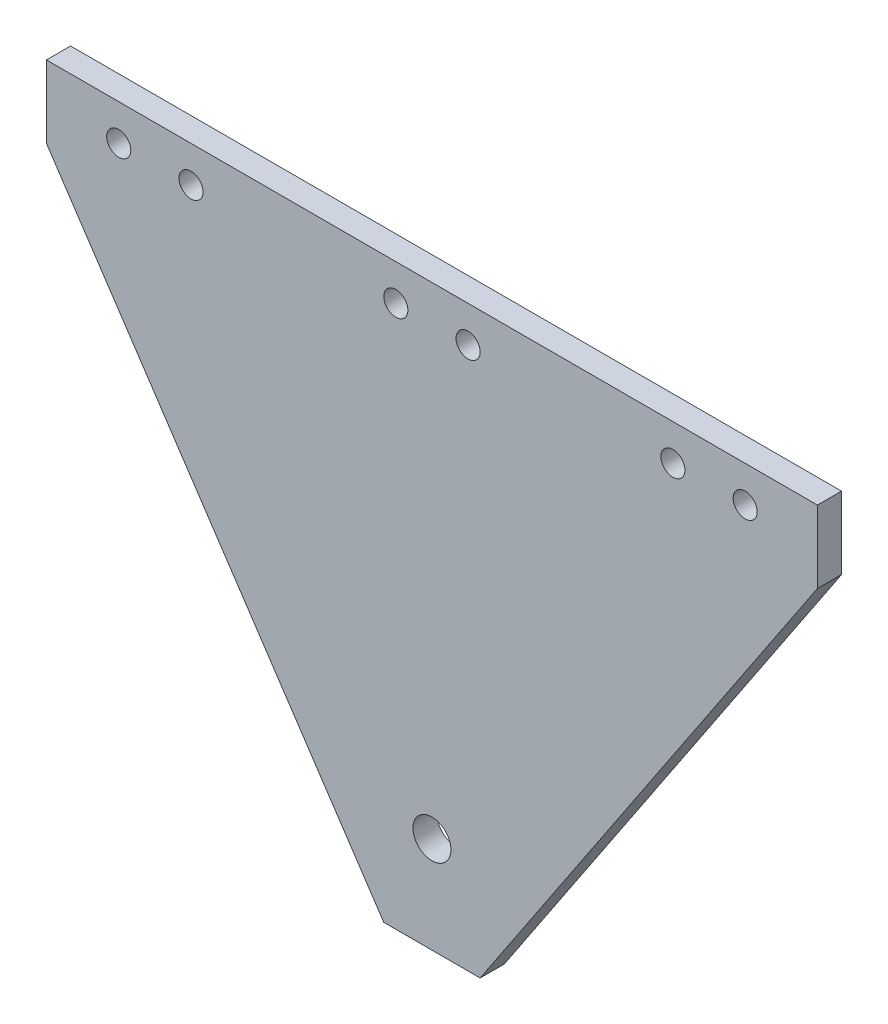
SolidWorks part; units mm, degrees
ref_plane "Front Plane" through (0, 0, 0) normal (0, 0, 1) x (1, 0, 0)
ref_plane "Top Plane" through (0, 0, 0) normal (0, 1, 0) x (1, 0, 0)
ref_plane "Right Plane" through (0, 0, 0) normal (1, 0, 0) x (0, 0, -1)
sketch "Sketch1" plane through (0, 0, 0) normal (0, 0, 1) x (1, 0, 0)
  line L2 (-50.8, -4.7625) -> (-50.8, 4.7625)
  line L3 (-50.8, 4.7625) -> (50.8, 4.7625)
  line L4 (50.8, -4.7625) -> (50.8, 4.7625)
  line L5 (-50.8, -4.7625) -> (50.8, 4.7625) construction
  line L6 (-50.8, 4.7625) -> (50.8, -4.7625) construction
  line L7 (-6.35, -71.4375) -> (6.35, -71.4375)
  line L8 (-50.8, -4.7625) -> (-6.35, -71.4375)
  line L9 (50.8, -4.7625) -> (6.35, -71.4375)
  circle A0 centre (4.7625, 0) radius 1.5875
  circle A1 centre (-4.7625, 0) radius 1.5875
  circle A2 centre (-41.275, 0) radius 1.5875
  circle A3 centre (-31.75, 0) radius 1.5875
  circle A4 centre (31.75, 0) radius 1.5875
  circle A5 centre (41.275, 0) radius 1.5875
  circle A6 centre (0, -58.7375) radius 2.5
  point P0 (0, 0)
  point P11 (0, -71.4375)
extrude "Boss-Extrude1" add sketch "Sketch1" along normal blind 3.175
